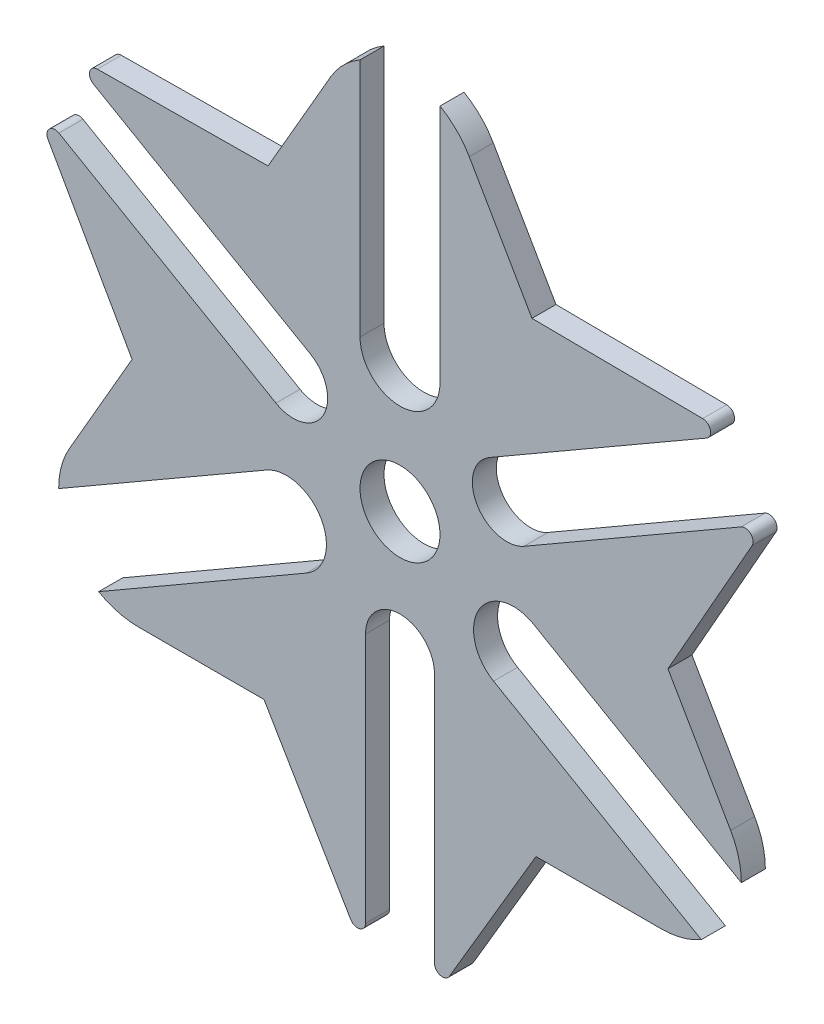
SolidWorks part; units mm, degrees
ref_plane "Front Plane" through (0, 0, 0) normal (0, 0, 1) x (1, 0, 0)
ref_plane "Top Plane" through (0, 0, 0) normal (0, 1, 0) x (1, 0, 0)
ref_plane "Right Plane" through (0, 0, 0) normal (1, 0, 0) x (0, 0, -1)
sketch "Sketch1" plane through (0, 0, 0) normal (0, 0, 1) x (1, 0, 0)
  line L0 (-5, 46.3953) -> (-5, 16.3953)
  line L1 (41.3397, -13.8675) -> (33.5, -0.2887)
  line L2 (-8.6603, 42.735) -> (-16.5, 29.1562)
  line L3 (-32.6795, -28.8675) -> (-17, -28.8675)
  line L4 (0, 0) -> (50, -28.8675) construction
  line L5 (5, 16.3953) -> (5, 46.3953)
  line L6 (37.6795, -27.5278) -> (11.6987, -12.5278)
  line L7 (50, -28.8675) -> (60.4789, -34.9175) construction
  line L8 (16.6987, -3.8675) -> (42.6795, -18.8675)
  line L9 (-42.6795, -18.8675) -> (-16.6987, -3.8675)
  line L10 (0, 0) -> (0, 85.6) construction
  line L11 (-11.6987, -12.5278) -> (-37.6795, -27.5278)
  line L12 (0, 0) -> (-74.1318, -42.8) construction
  line L13 (60.4789, -34.9175) -> (0, 69.7958) construction
  line L14 (0, 69.7958) -> (-60.4449, -34.8979) construction
  line L15 (-60.4449, -34.8979) -> (60.4789, -34.9175) construction
  line L16 (16.5, 29.1562) -> (41.5099, 28.9407)
  line L17 (45.8183, 21.4783) -> (33.5, -0.2887)
  line L18 (41.5099, 28.9407) -> (11.199, 11.4407)
  line L19 (45.8183, 21.4783) -> (15.5074, 3.9783)
  line L20 (17, -28.8675) -> (4.3084, -50.4189)
  line L21 (16.5, 29.1562) -> (8.6603, 42.735)
  line L22 (4.3084, -50.4189) -> (4.3084, -15.4189)
  line L23 (-4.3084, -50.4189) -> (-4.3084, -15.4189)
  line L24 (-4.3084, -50.4189) -> (-17, -28.8675)
  line L25 (-33.5, -0.2887) -> (-45.8183, 21.4783)
  line L26 (-45.8183, 21.4783) -> (-15.5074, 3.9783)
  line L27 (-41.5099, 28.9407) -> (-11.199, 11.4407)
  line L28 (-41.5099, 28.9407) -> (-16.5, 29.1562)
  line L29 (-33.5, -0.2887) -> (-41.3397, -13.8675)
  line L31 (17, -28.8675) -> (32.6795, -28.8675)
  circle A0 centre (0, 0) radius 28.8675 construction
  arc A1 (8.6603, 42.735) -> (5, 46.3953) centre (0, 37.735) ccw
  arc A2 (32.6795, -28.8675) -> (37.6795, -27.5278) centre (32.6795, -18.8675) ccw
  arc A3 (-41.3397, -13.8675) -> (-42.6795, -18.8675) centre (-32.6795, -18.8675) ccw
  circle A4 centre (0, 0) radius 5
  arc A5 (-16.6987, -3.8675) -> (-11.6987, -12.5278) centre (-14.1987, -8.1976) cw
  arc A6 (11.6987, -12.5278) -> (16.6987, -3.8675) centre (14.1987, -8.1976) cw
  arc A7 (-5, 16.3953) -> (5, 16.3953) centre (0, 16.3953) ccw
  arc A8 (-37.6795, -27.5278) -> (-32.6795, -28.8675) centre (-32.6795, -18.8675) ccw
  arc A9 (42.6795, -18.8675) -> (41.3397, -13.8675) centre (32.6795, -18.8675) ccw
  arc A10 (-5, 46.3953) -> (-8.6603, 42.735) centre (0, 37.735) ccw
  circle A12 centre (0, 0) radius 57.735 construction
  arc A13 (4.3084, -15.4189) -> (-4.3084, -15.4189) centre (0, -15.4189) ccw
  arc A14 (11.199, 11.4407) -> (15.5074, 3.9783) centre (13.3532, 7.7095) ccw
  arc A15 (-15.5074, 3.9783) -> (-11.199, 11.4407) centre (-13.3532, 7.7095) ccw
  point P10 (50, -28.8675)
  point P13 (-50, -28.8675)
  point P30 (-50, -28.8675)
  point P31 (50, -28.8675)
  point P48 (50, 28.8675)
  point P68 (0, 0)
  dimension "D2" = 10
  dimension "D3" = 10
  dimension "D4" = 10
  dimension "D5" = 30
  dimension "D14" = 69.7958
  dimension "D20" = 35
  dimension "D22" = 4.3084
  dimension "D1" = 100
  dimension "D6" = 30
  dimension "D7" = 30
  dimension "D8" = 120
  dimension "D9" = 120
  dimension "D10" = 10
  dimension "D11" = 10
  dimension "D12" = 10
  dimension "D13" = 12.1
  dimension "D15" = 69.7958
  dimension "D16" = 120
  dimension "D17" = 17
  dimension "D18" = 17
  dimension "D19" = 29.1562
  dimension "D21" = 35
  dimension "D23" = 15.6795
  dimension "D25" = 15.6795
  dimension "D24" = 3
extrude "Boss-Extrude1" add sketch "Sketch1" along normal blind 3
fillet "Fillet1" radius 1 6 edges at (-45.8183, 21.4783, 1.5) (-41.5099, 28.9407, 1.5) (4.3084, -50.4189, 1.5) (-4.3084, -50.4189, 1.5) (45.8183, 21.4783, 1.5) (41.5099, 28.9407, 1.5)
